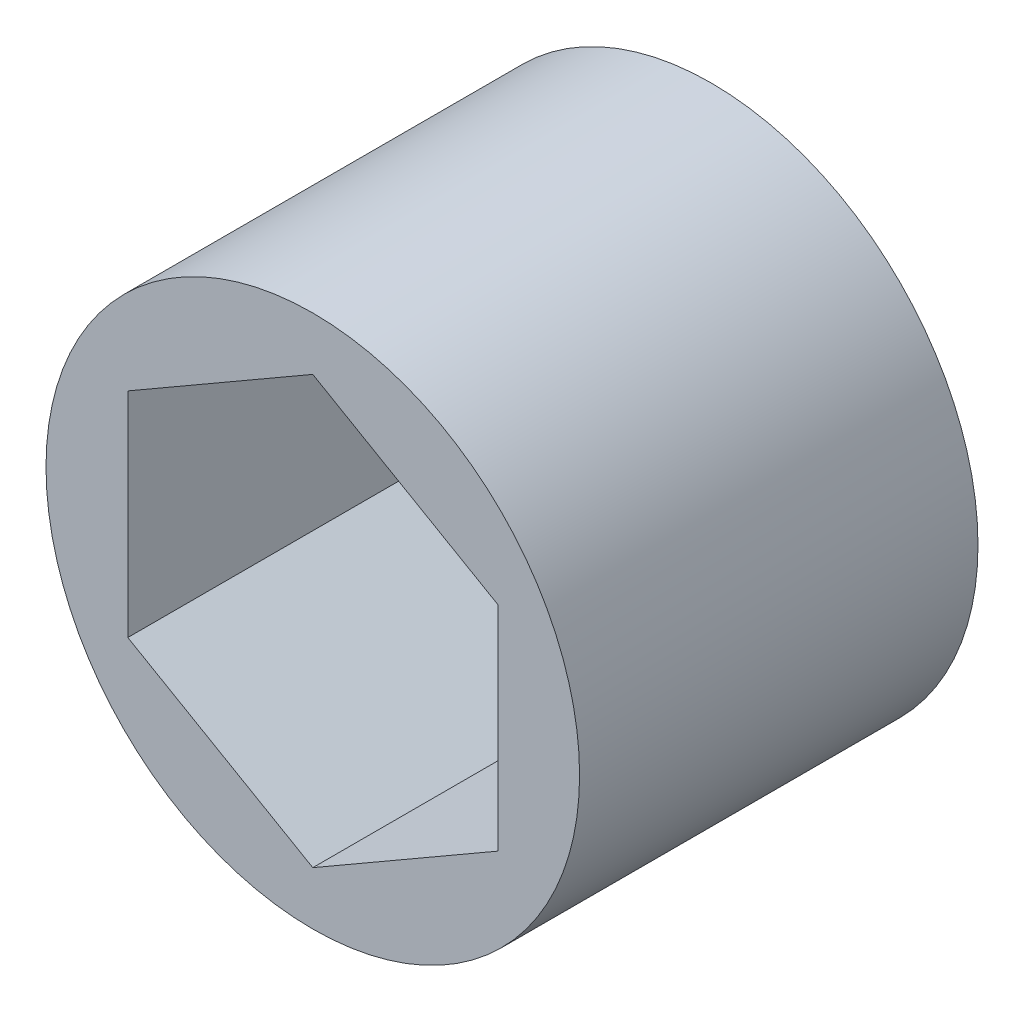
SolidWorks part; units mm, degrees
material "PET"
ref_plane "Front Plane" through (0, 0, 0) normal (0, 0, 1) x (1, 0, 0)
ref_plane "Top Plane" through (0, 0, 0) normal (0, 1, 0) x (1, 0, 0)
ref_plane "Right Plane" through (0, 0, 0) normal (1, 0, 0) x (0, 0, -1)
sketch "Sketch1" plane through (0, 0, 0) normal (0, 0, 1) x (1, 0, 0)
  line L1 (0, 7.6256) -> (-6.604, 3.8128)
  line L2 (-6.604, 3.8128) -> (-6.604, -3.8128)
  line L3 (-6.604, -3.8128) -> (0, -7.6256)
  line L4 (0, -7.6256) -> (6.604, -3.8128)
  line L5 (6.604, -3.8128) -> (6.604, 3.8128)
  line L6 (6.604, 3.8128) -> (0, 7.6256)
  circle A0 centre (0, 0) radius 6.604 construction
  circle A1 centre (0, 0) radius 9.525
  dimension "D1" = 13.208
  dimension "D2" = 19.05
extrude "Boss-Extrude1" add sketch "Sketch1" along normal mid plane 14.224
